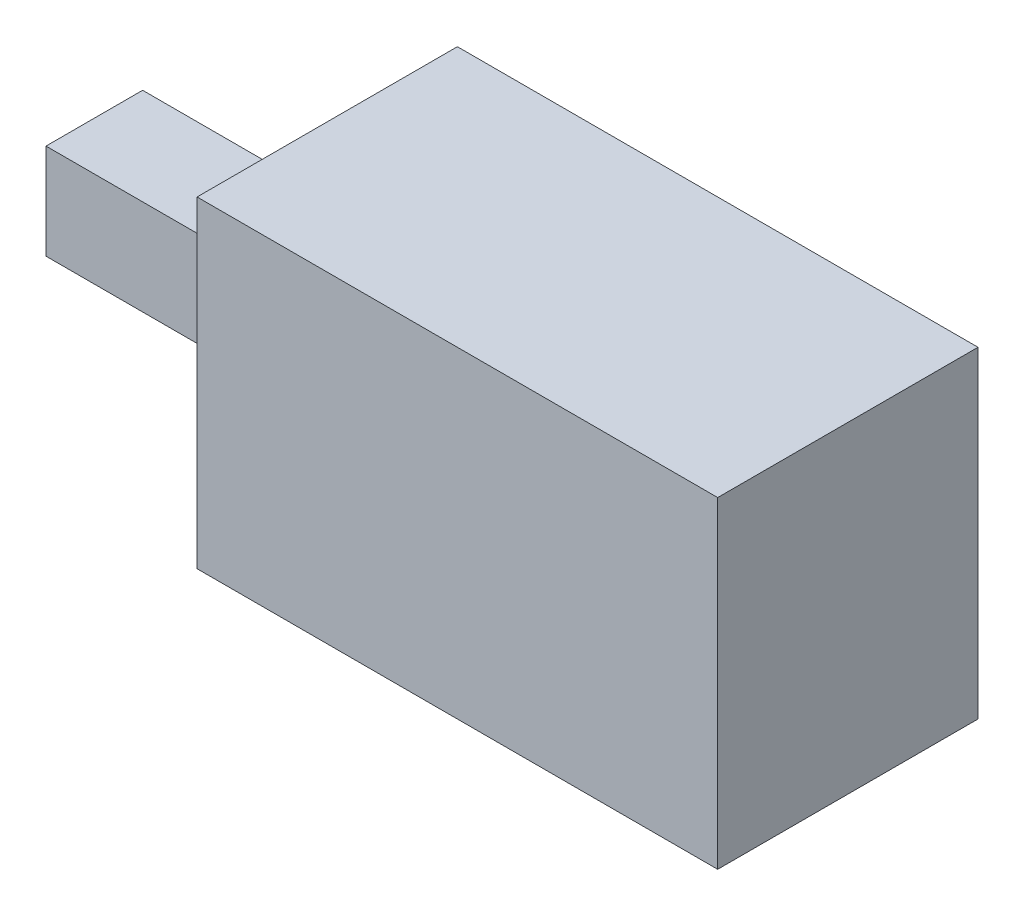
SolidWorks part; units mm, degrees
ref_plane "Front Plane" through (0, 0, 0) normal (0, 0, 1) x (1, 0, 0)
ref_plane "Top Plane" through (0, 0, 0) normal (0, 1, 0) x (1, 0, 0)
ref_plane "Right Plane" through (0, 0, 0) normal (1, 0, 0) x (0, 0, -1)
sketch "Sketch1" plane through (0, 0, 0) normal (0, 1, 0) x (1, 0, 0)
  line L1 (-38, 19) -> (38, 19)
  line L2 (-38, 19) -> (-38, -19)
  line L3 (-38, -19) -> (38, -19)
  line L4 (38, 19) -> (38, -19)
  line L5 (-38, 19) -> (38, -19) construction
  line L6 (-38, -19) -> (38, 19) construction
  point P0 (0, 0)
  dimension "D1" = 38
  dimension "D2" = 76
extrude "Boss-Extrude1" add sketch "Sketch1" along normal blind 47
sketch "Sketch2" plane through (-38, 0, 0) normal (-1, 0, 0) x (0, 0, 1)
  line L1 (-7.0532, 30.4622) -> (7.0532, 30.4622)
  line L2 (-7.0532, 30.4622) -> (-7.0532, 16.5378)
  line L3 (-7.0532, 16.5378) -> (7.0532, 16.5378)
  line L4 (7.0532, 30.4622) -> (7.0532, 16.5378)
  line L5 (-7.0532, 30.4622) -> (7.0532, 16.5378) construction
  line L6 (-7.0532, 16.5378) -> (7.0532, 30.4622) construction
  point P0 (0, 23.5)
extrude "Boss-Extrude2" add sketch "Sketch2" along normal blind 34
